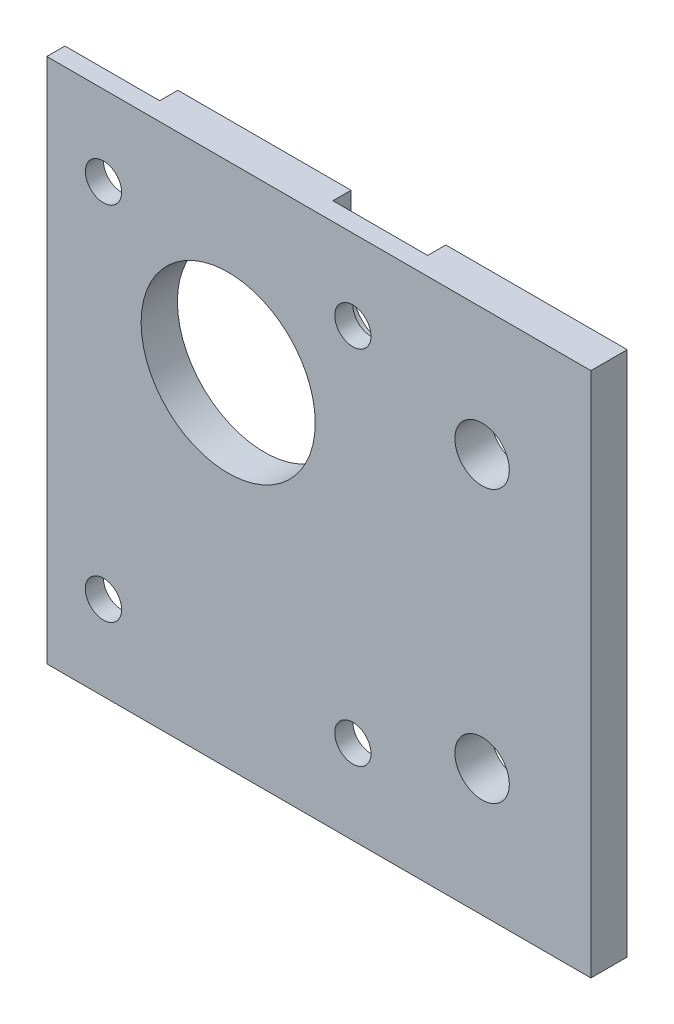
SolidWorks part; units mm, degrees
ref_plane "Front Plane" through (0, 0, 0) normal (0, 0, 1) x (1, 0, 0)
ref_plane "Top Plane" through (0, 0, 0) normal (0, 1, 0) x (1, 0, 0)
ref_plane "Right Plane" through (0, 0, 0) normal (1, 0, 0) x (0, 0, -1)
sketch "Sketch1" plane through (0, 0, 0) normal (0, 0, 1) x (1, 0, 0)
  line L0 (-13.75, -19.7) -> (-9.6769, -16.8) construction
  line L3 (20, 29) -> (40, 29)
  line L8 (20, -29) -> (-20, -29)
  line L9 (20, -29) -> (20, 29) construction
  line L10 (40, 29) -> (40, -29)
  line L11 (20, 29) -> (-20, 29)
  line L14 (-20, -29) -> (-20, 29)
  line L15 (20, -29) -> (-20, 29) construction
  line L16 (20, 29) -> (-20, -29) construction
  line L17 (-16.186, -16.2786) -> (-12.1129, -13.3786)
  line L18 (-11.314, -23.1214) -> (-7.2409, -20.2214)
  line L19 (0, -29) -> (0, 29) construction
  line L22 (40, -29) -> (20, -29)
  line L23 (13.75, -15.5) -> (20, -15.5)
  line L24 (9.55, -19.7) -> (9.55, -29)
  line L25 (-9.55, 20.15) -> (-9.55, 29)
  line L26 (-13.75, 15.95) -> (-20, 15.95)
  line L27 (9.55, 20.15) -> (9.55, 29)
  line L28 (13.75, 15.95) -> (20, 15.95)
  line L29 (20, 15.95) -> (20, 29)
  line L30 (-16.186, -16.2786) -> (-20, -16.2786)
  line L31 (20, -29) -> (20, -15.5)
  line L32 (-11.314, -29) -> (-11.314, -23.1214)
  circle A18 centre (-13.75, 20.15) radius 4.2
  circle A19 centre (13.75, 20.15) radius 4.2
  circle A20 centre (13.75, -19.7) radius 4.2
  arc A21 (-16.186, -16.2786) -> (-11.314, -23.1214) centre (-13.75, -19.7) ccw
  arc A22 (-7.2409, -20.2214) -> (-12.1129, -13.3786) centre (-9.6769, -16.8) ccw
  circle A23 centre (0, 8.8) radius 9.6
  circle A24 centre (-5.725, -6.1) radius 4.2
  circle A25 centre (5.725, -6.1) radius 4.2
  point P0 (0, 0)
  point P14 (-6.2555, -14.364)
  point P31 (-11.7135, -18.25)
  point P37 (5.725, -10.3)
  point P43 (20, 29)
  point P46 (-20, 29)
  dimension "D1" = 58
  dimension "D2" = 40
  dimension "D3" = 12.2
  dimension "D4" = 8.4
  dimension "D5" = 8.4
  dimension "D6" = 19.2
  dimension "D7" = 9.3
  dimension "D8" = 27.5
  dimension "D9" = 39.85
  dimension "D10" = 5
  dimension "D12" = 20.2
  dimension "D13" = 11.45
  dimension "D14" = 22.9
  dimension "D15" = 20
extrude "Boss-Extrude1" add sketch "Sketch1" along normal blind 2
sketch "Sketch4" plane through (0, 0, 2) normal (0, 0, 1) x (1, 0, 0)
  line L0 (0, -29) -> (0, 29) construction
  line L6 (40, -29) -> (20, -29) construction
  line L8 (-20, -29) -> (40, -29)
  line L11 (40, -29) -> (40, 29)
  line L12 (-20, 29) -> (-20, -29)
  line L13 (-20, -16.2786) -> (-20, 15.95) construction
  line L14 (-20, 29) -> (40, 29)
  line L15 (20, 29) -> (40, 29) construction
  line L16 (40, 29) -> (40, -29) construction
  circle A2 centre (13.75, -19.7) radius 2
  circle A3 centre (-13.75, 20.15) radius 2
  circle A4 centre (13.75, 20.15) radius 2
  circle A10 centre (-13.75, -19.7) radius 2
  circle A11 centre (0, 8.8) radius 9.6
  circle A12 centre (0, 8.8) radius 9.6 construction
  dimension "D1" = 4
extrude "Boss-Extrude3" add sketch "Sketch4" along normal blind 2
sketch "Sketch5" plane through (0, 0, 4) normal (0, 0, 1) x (1, 0, 0)
  line L0 (-20, 0) -> (40, 0) construction
  line L3 (-20, 29) -> (-20, -29) construction
  line L4 (40, -29) -> (40, 29) construction
  circle A0 centre (28, 15) radius 3
  circle A1 centre (28, -15) radius 3
  point P3 (0, 0)
  point P6 (27.2291, 15)
  point P7 (12.0293, -0.5645)
  point P9 (41.2573, 17.5641)
  point P10 (40.8769, 14.4355)
  point P13 (0, 0)
  point P14 (-20, -0.8488)
  point P17 (12.0293, -0.5645)
  point P20 (40, 0)
  point P23 (0, 0)
  dimension "D1" = 6
  dimension "D2" = 15
  dimension "D3" = 12
extrude "Cut-Extrude1" cut sketch "Sketch5" against normal blind 4
